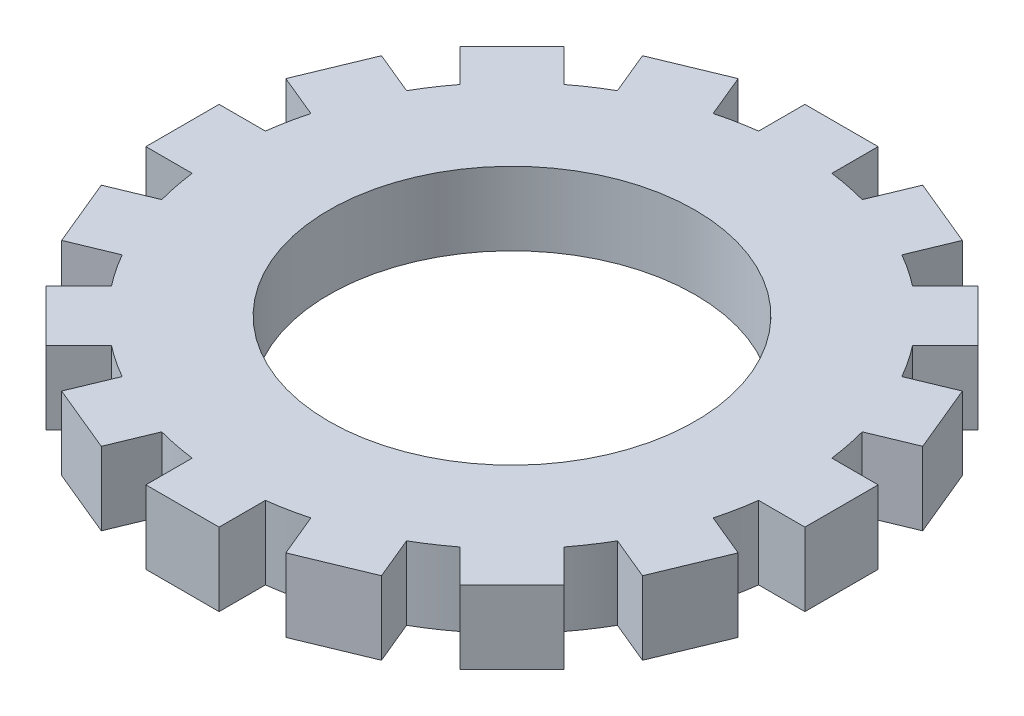
SolidWorks part; units mm, degrees
ref_plane "Front Plane" through (0, 0, 0) normal (0, 0, 1) x (1, 0, 0)
ref_plane "Top Plane" through (0, 0, 0) normal (0, 1, 0) x (1, 0, 0)
ref_plane "Right Plane" through (0, 0, 0) normal (1, 0, 0) x (0, 0, -1)
sketch "Sketch1" plane through (0, 0, 0) normal (0, 1, 0) x (1, 0, 0)
  line L0 (12.6014, 43.488) -> (10.1821, 37.6474)
  line L1 (-5, 45) -> (5, 45)
  line L2 (-5, 45) -> (-5, 38.6782)
  line L4 (5, 45) -> (5, 38.6782)
  line L5 (-5, 45) -> (5, 38.6782) construction
  line L6 (-5, 38.6782) -> (5, 45) construction
  line L7 (12.6014, 43.488) -> (21.8402, 39.6612)
  line L8 (21.8402, 39.6612) -> (19.4209, 33.8205)
  line L9 (28.2843, 35.3553) -> (23.8141, 30.8851)
  line L10 (28.2843, 35.3553) -> (35.3553, 28.2843)
  line L11 (35.3553, 28.2843) -> (30.8851, 23.8141)
  line L12 (39.6612, 21.8402) -> (33.8205, 19.4209)
  line L13 (39.6612, 21.8402) -> (43.488, 12.6014)
  line L14 (43.488, 12.6014) -> (37.6474, 10.1821)
  line L15 (45, 5) -> (38.6782, 5)
  line L16 (45, 5) -> (45, -5)
  line L17 (45, -5) -> (38.6782, -5)
  line L18 (43.488, -12.6014) -> (37.6474, -10.1821)
  line L19 (43.488, -12.6014) -> (39.6612, -21.8402)
  line L20 (39.6612, -21.8402) -> (33.8205, -19.4209)
  line L21 (35.3553, -28.2843) -> (30.8851, -23.8141)
  line L22 (35.3553, -28.2843) -> (28.2843, -35.3553)
  line L23 (28.2843, -35.3553) -> (23.8141, -30.8851)
  line L24 (21.8402, -39.6612) -> (19.4209, -33.8205)
  line L25 (21.8402, -39.6612) -> (12.6014, -43.488)
  line L26 (12.6014, -43.488) -> (10.1821, -37.6474)
  line L27 (5, -45) -> (5, -38.6782)
  line L28 (5, -45) -> (-5, -45)
  line L29 (-5, -45) -> (-5, -38.6782)
  line L30 (-12.6014, -43.488) -> (-10.1821, -37.6474)
  line L31 (-12.6014, -43.488) -> (-21.8402, -39.6612)
  line L32 (-21.8402, -39.6612) -> (-19.4209, -33.8205)
  line L33 (-28.2843, -35.3553) -> (-23.8141, -30.8851)
  line L34 (-28.2843, -35.3553) -> (-35.3553, -28.2843)
  line L35 (-35.3553, -28.2843) -> (-30.8851, -23.8141)
  line L36 (-39.6612, -21.8402) -> (-33.8205, -19.4209)
  line L37 (-39.6612, -21.8402) -> (-43.488, -12.6014)
  line L38 (-43.488, -12.6014) -> (-37.6474, -10.1821)
  line L39 (-45, -5) -> (-38.6782, -5)
  line L40 (-45, -5) -> (-45, 5)
  line L41 (-45, 5) -> (-38.6782, 5)
  line L42 (-43.488, 12.6014) -> (-37.6474, 10.1821)
  line L43 (-43.488, 12.6014) -> (-39.6612, 21.8402)
  line L44 (-39.6612, 21.8402) -> (-33.8205, 19.4209)
  line L45 (-35.3553, 28.2843) -> (-30.8851, 23.8141)
  line L46 (-35.3553, 28.2843) -> (-28.2843, 35.3553)
  line L47 (-28.2843, 35.3553) -> (-23.8141, 30.8851)
  line L48 (-21.8402, 39.6612) -> (-19.4209, 33.8205)
  line L49 (-21.8402, 39.6612) -> (-12.6014, 43.488)
  line L50 (-12.6014, 43.488) -> (-10.1821, 37.6474)
  circle A0 centre (0, 0) radius 25
  arc A1 (-5, 38.6782) -> (-10.1821, 37.6474) centre (0, 0) ccw
  arc A3 (10.1821, 37.6474) -> (5, 38.6782) centre (0, 0) ccw
  arc A4 (23.8141, 30.8851) -> (19.4209, 33.8205) centre (0, 0) ccw
  arc A5 (33.8205, 19.4209) -> (30.8851, 23.8141) centre (0, 0) ccw
  arc A6 (38.6782, 5) -> (37.6474, 10.1821) centre (0, 0) ccw
  arc A7 (37.6474, -10.1821) -> (38.6782, -5) centre (0, 0) ccw
  arc A8 (30.8851, -23.8141) -> (33.8205, -19.4209) centre (0, 0) ccw
  arc A9 (19.4209, -33.8205) -> (23.8141, -30.8851) centre (0, 0) ccw
  arc A10 (5, -38.6782) -> (10.1821, -37.6474) centre (0, 0) ccw
  arc A11 (-10.1821, -37.6474) -> (-5, -38.6782) centre (0, 0) ccw
  arc A12 (-23.8141, -30.8851) -> (-19.4209, -33.8205) centre (0, 0) ccw
  arc A13 (-33.8205, -19.4209) -> (-30.8851, -23.8141) centre (0, 0) ccw
  arc A14 (-38.6782, -5) -> (-37.6474, -10.1821) centre (0, 0) ccw
  arc A15 (-37.6474, 10.1821) -> (-38.6782, 5) centre (0, 0) ccw
  arc A16 (-30.8851, 23.8141) -> (-33.8205, 19.4209) centre (0, 0) ccw
  arc A17 (-19.4209, 33.8205) -> (-23.8141, 30.8851) centre (0, 0) ccw
  point P4 (0, 41.8391)
  point P72 (0, 0)
  dimension "D1" = 50
  dimension "D2" = 78
  dimension "D3" = 45
  dimension "D4" = 10
  dimension "D5" = 16
extrude "Boss-Extrude1" add sketch "Sketch1" along normal blind 10
